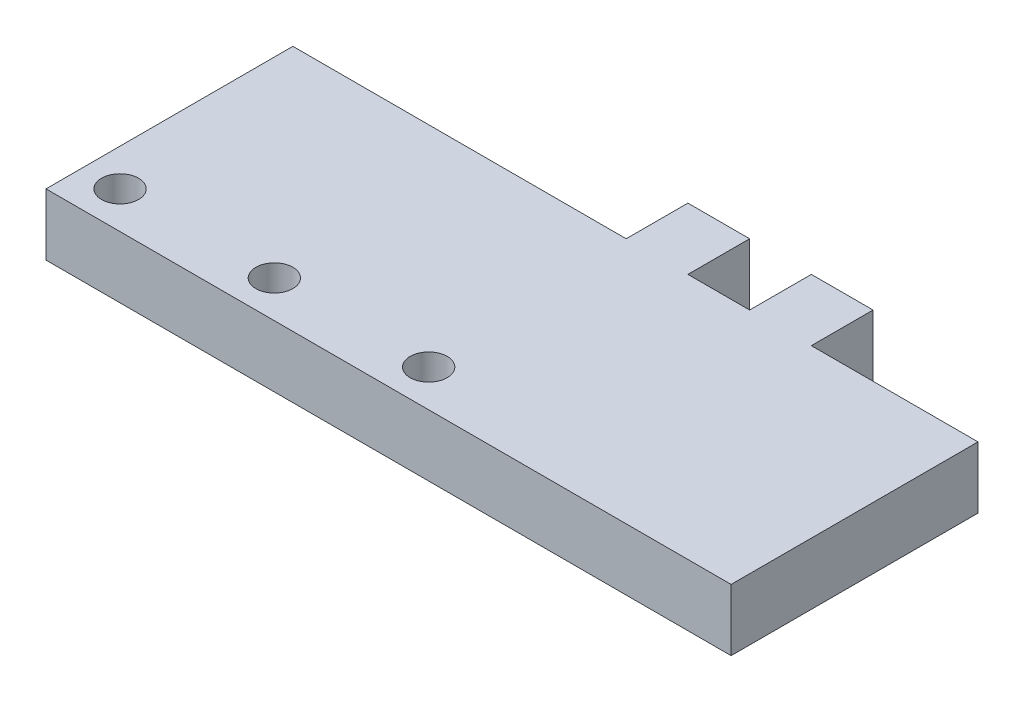
SolidWorks part; units mm, degrees
ref_plane "Front Plane" through (0, 0, 0) normal (0, 0, 1) x (1, 0, 0)
ref_plane "Top Plane" through (0, 0, 0) normal (0, 1, 0) x (1, 0, 0)
ref_plane "Right Plane" through (0, 0, 0) normal (1, 0, 0) x (0, 0, -1)
sketch "Sketch1" plane through (0, 0, 0) normal (0, 1, 0) x (1, 0, 0)
  line L0 (23.4845, 27.298) -> (33.4845, 27.298)
  line L1 (-40.5155, -12.702) -> (70.4845, -12.702)
  line L2 (-40.5155, -12.702) -> (-40.5155, 27.298)
  line L3 (-40.5155, 27.298) -> (13.4845, 27.298)
  line L4 (70.4845, -12.702) -> (70.4845, 27.298)
  line L6 (13.4845, 27.298) -> (13.4845, 37.298)
  line L7 (13.4845, 37.298) -> (23.4845, 37.298)
  line L8 (23.4845, 27.298) -> (23.4845, 37.298)
  line L10 (33.4845, 27.298) -> (33.4845, 37.298)
  line L11 (33.4845, 37.298) -> (43.4845, 37.298)
  line L12 (43.4845, 27.298) -> (43.4845, 37.298)
  line L13 (43.4845, 27.298) -> (70.4845, 27.298)
  circle A0 centre (-34.5155, -6.702) radius 3
  circle A1 centre (-9.5155, -6.702) radius 3
  circle A2 centre (15.4845, -6.702) radius 3
  dimension "D1" = 6
  dimension "D2" = 6
  dimension "D3" = 6
  dimension "D4" = 6
  dimension "D5" = 80
  dimension "D7" = 6
  dimension "D8" = 25
  dimension "D9" = 25
  dimension "D6" = 40
  dimension "D10" = 10
  dimension "D11" = 10
  dimension "D12" = 10
  dimension "D13" = 10
  dimension "D14" = 10
  dimension "D15" = 54
extrude "Boss-Extrude1" add sketch "Sketch1" along normal blind 10
sketch "Sketch2" plane through (0, 0, -27.298) normal (0, 0, -1) x (-1, 0, 0)
  line L0 (-23.4845, 0) -> (-33.4845, 10) construction
  point P4 (-28.4845, 5)
hole_wizard "M3x0.5 Tapped Hole1" positions "Sketch3" profile "Sketch4" tap size "M3x0.5" standard "BSI"
sketch "Sketch3" plane through (0, 0, -27.298) normal (0, 0, -1) x (-1, 0, 0)
  point P0 (-28.4845, 5)
sketch "Sketch4" plane through (28.4845, 5, -27.298) normal (1, 0, 0) x (0, 1, 0)
  line L0 (0, 0) -> (0, 5.7511)
  line L1 (0, 5.7511) -> (1.25, 5)
  line L2 (1.25, 5) -> (1.25, 0)
  line L5 (1.25, 0) -> (0, 0)
  line L10 (0, 5.7511) -> (-1.25, 5) construction
  line L11 (0, -6.35) -> (0, 107.95) construction
  dimension "Tap Drill Dia." = 2.5
  dimension "Tap Drill Depth" = 5
  dimension "Drill Angle" = 118
cosmetic thread "Hole Thread1" parameters "D1"=6, "D2"=3
